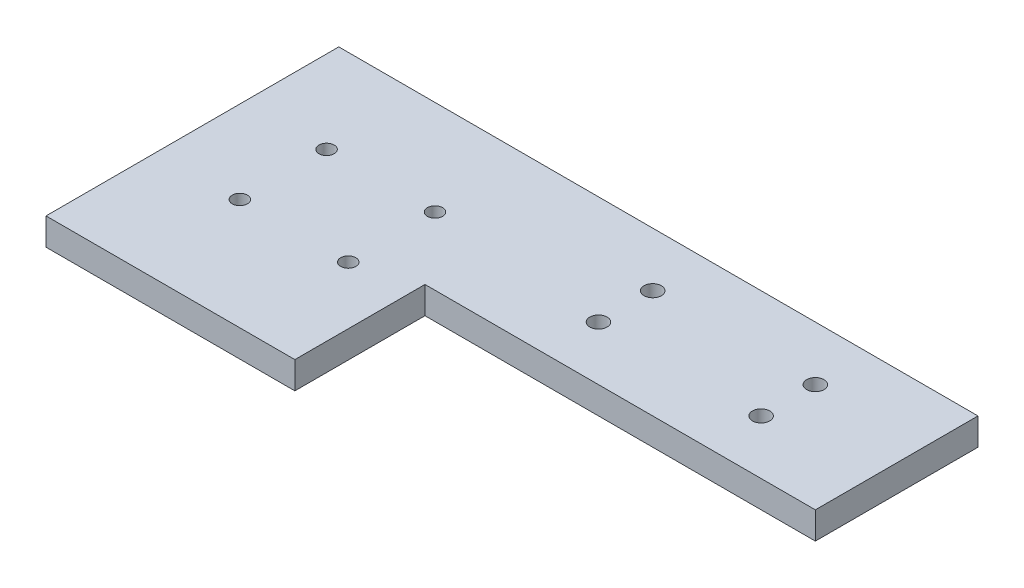
SolidWorks part; units mm, degrees
ref_plane "Front Plane" through (0, 0, 0) normal (0, 0, 1) x (1, 0, 0)
ref_plane "Top Plane" through (0, 0, 0) normal (0, 1, 0) x (1, 0, 0)
ref_plane "Right Plane" through (0, 0, 0) normal (1, 0, 0) x (0, 0, -1)
sketch "Sketch1" plane through (0, 0, 0) normal (0, 1, 0) x (1, 0, 0)
  line L1 (0, 0) -> (-37.9, 0)
  line L2 (0, 0) -> (0, -30)
  line L4 (-37.9, 0) -> (-37.9, -35)
  line L5 (0, 0) -> (80, 0)
  line L6 (0, 0) -> (0, -30)
  line L7 (0, -30) -> (80, -30)
  line L8 (80, 0) -> (80, -30)
  line L10 (-37.9, -35) -> (-37.9, -54)
  line L11 (-37.9, -54) -> (0, -54)
  line L12 (0, -30) -> (0, -54)
  line L13 (0, -30) -> (8, -30)
  line L14 (0, -30) -> (0, -54)
  line L15 (0, -54) -> (8, -54)
  line L16 (8, -30) -> (8, -54)
  circle A0 centre (30, -20) radius 1.6
  circle A1 centre (60, -20) radius 1.6
  circle A2 centre (60, -10) radius 1.6
  circle A3 centre (30, -10) radius 1.6
  circle A4 centre (-22.65, -17.5) radius 1.4
  circle A5 centre (-2.65, -17.5) radius 1.4
  circle A6 centre (-2.65, -33.5) radius 1.4
  circle A7 centre (-22.65, -33.5) radius 1.4
  dimension "D5" = 3.2
  dimension "D6" = 10
  dimension "D7" = 30
  dimension "D10" = 10
  dimension "D11" = 30
  dimension "D12" = 17.5
  dimension "D13" = 15.25
  dimension "D14" = 2.8
  dimension "D18" = 20
  dimension "D19" = 16
  dimension "D1" = 37.9
  dimension "D2" = 30
  dimension "D3" = 80
  dimension "D4" = 54
  dimension "D15" = 8
  dimension "D8" = 2
  dimension "D9" = 2
  dimension "D16" = 2
  dimension "D17" = 2
extrude "Boss-Extrude1" add sketch "Sketch1" along normal blind 5 contours L8 L5 L2 L7 | L12 L2 L1 L4 L10 L11 | L16 L7 L12 L15
